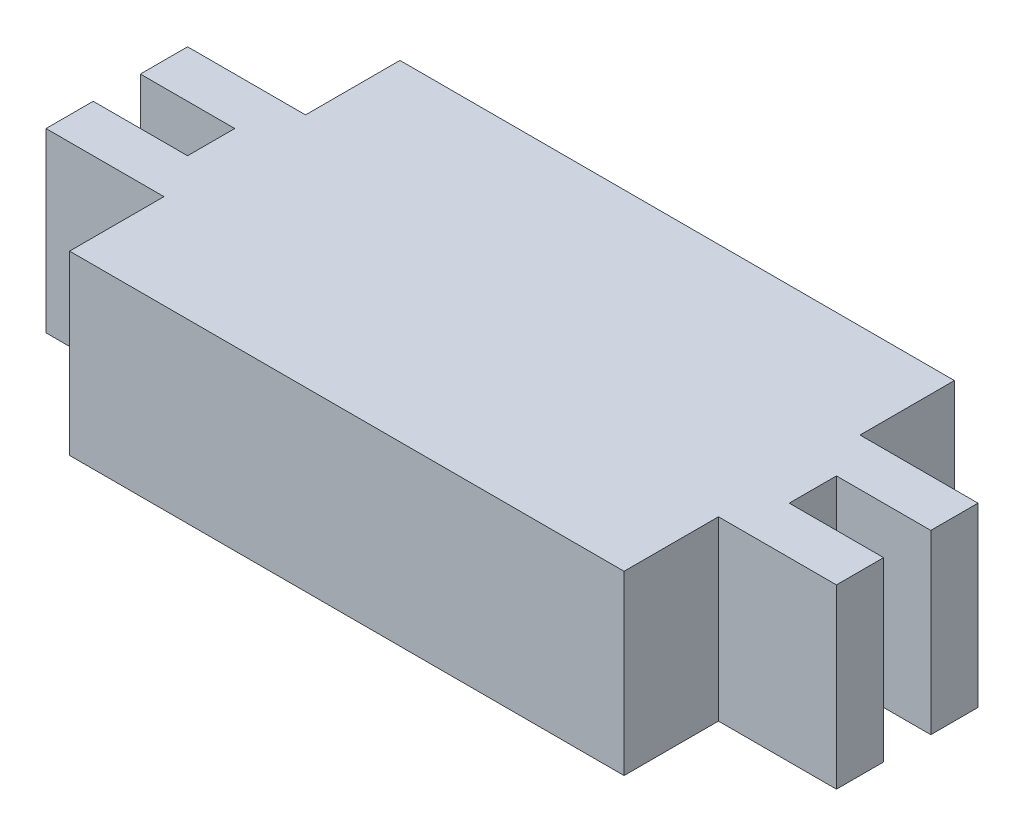
SolidWorks part; units mm, degrees
ref_plane "Plan de face" through (0, 0, 0) normal (0, 0, 1) x (1, 0, 0)
ref_plane "Plan de dessus" through (0, 0, 0) normal (0, 1, 0) x (1, 0, 0)
ref_plane "Plan de droite" through (0, 0, 0) normal (1, 0, 0) x (0, 0, -1)
sketch "Esquisse1" plane through (0, 0, 0) normal (0, 1, 0) x (1, 0, 0)
  line L0 (23.5, 6) -> (23.5, 14)
  line L1 (-23.5, -14) -> (23.5, -14)
  line L2 (-23.5, -14) -> (-23.5, -6)
  line L3 (-23.5, 14) -> (23.5, 14)
  line L4 (23.5, -14) -> (23.5, -6)
  line L5 (-23.5, -14) -> (23.5, 14) construction
  line L6 (-23.5, 14) -> (23.5, -14) construction
  line L7 (-23.5, 6) -> (-33.5, 6)
  line L9 (-23.5, -6) -> (-33.5, -6)
  line L10 (-33.5, 6) -> (-33.5, 2)
  line L11 (23.5, 6) -> (33.5, 6)
  line L13 (23.5, -6) -> (33.5, -6)
  line L14 (33.5, 6) -> (33.5, 2)
  line L15 (-23.5, 6) -> (-23.5, 14)
  line L16 (-33.5, -2) -> (-33.5, -6)
  line L17 (-33.5, 2) -> (-25.5, 2)
  line L19 (-33.5, -2) -> (-25.5, -2)
  line L20 (-25.5, 2) -> (-25.5, -2)
  line L21 (33.5, -2) -> (33.5, -6)
  line L22 (33.5, -2) -> (25.5, -2)
  line L24 (33.5, 2) -> (25.5, 2)
  line L25 (25.5, -2) -> (25.5, 2)
  point P0 (0, 0)
  dimension "D1" = 47
  dimension "D2" = 28
  dimension "D3" = 12
  dimension "D4" = 10
  dimension "D5" = 8
  dimension "D6" = 4
extrude "Boss.-Extru.1" add sketch "Esquisse1" along normal blind 15
